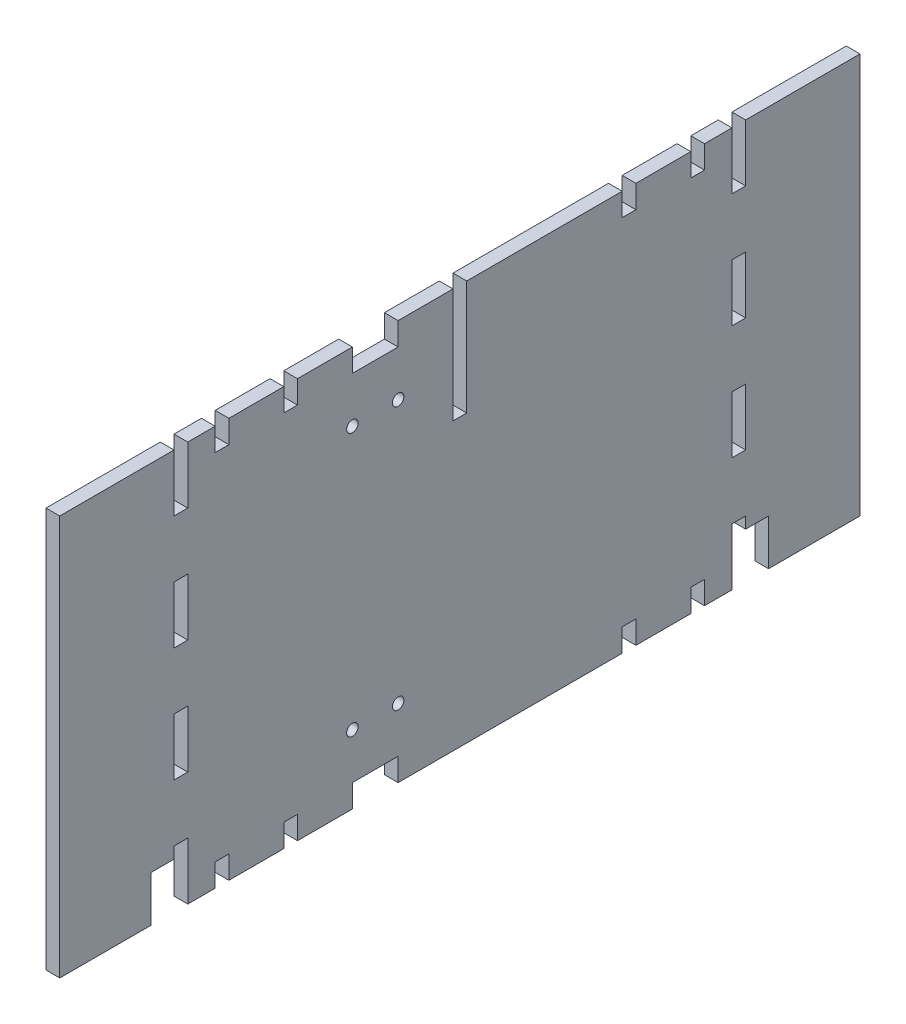
SolidWorks part; units mm, degrees
ref_plane "Front" through (0, 0, 0) normal (0, 0, 1) x (1, 0, 0)
ref_plane "Top" through (0, 0, 0) normal (0, 1, 0) x (1, 0, 0)
ref_plane "Right" through (0, 0, 0) normal (1, 0, 0) x (0, 0, -1)
sketch "Sketch1" plane through (0, 0, 0) normal (1, 0, 0) x (0, 0, -1)
  line L1 (0, 0) -> (-350, 0)
  line L2 (0, 0) -> (0, 175)
  line L3 (0, 175) -> (-350, 175)
  line L4 (-350, 0) -> (-350, 175)
  dimension "D1" = 350
  dimension "D2" = 175
extrude "Boss-Extrude1" add sketch "Sketch1" along normal blind 6
ref_plane "Plane1" through (0, 0, 175) normal (0, 0, 1) x (1, 0, 0)
sketch "Sketch3" plane through (6, 0, 0) normal (1, 0, 0) x (0, 0, -1)
  line L0 (-350, 175) -> (-350, 0) construction
  line L1 (-300, 175) -> (-294, 175)
  line L2 (-300, 175) -> (-300, 150)
  line L3 (-300, 150) -> (-294, 150)
  line L4 (-294, 175) -> (-294, 150)
  line L5 (0, 175) -> (-350, 175) construction
  dimension "D1" = 6
  dimension "D2" = 25
  dimension "D3" = 50
extrude "Cut-Extrude1" cut sketch "Sketch3" against normal through all
pattern_linear "LPattern1" count 4 spacing 50 along (0, -1, 0) of "Cut-Extrude1"
sketch "Sketch4" plane through (6, 0, 0) normal (1, 0, 0) x (0, 0, -1)
  line L0 (0, 175) -> (-294, 175) construction
  line L1 (-282, 175) -> (-276, 175)
  line L2 (-282, 175) -> (-282, 165)
  line L3 (-282, 165) -> (-276, 165)
  line L4 (-276, 175) -> (-276, 165)
  line L5 (-294, 150) -> (-294, 175) construction
  dimension "D1" = 6
  dimension "D2" = 12
  dimension "D3" = 10
extrude "Cut-Extrude2" cut sketch "Sketch4" against normal through all
pattern_linear "LPattern2" count 2 spacing 165 along (0, -1, 0) of "Cut-Extrude2"
sketch "Sketch5" plane through (6, 0, 0) normal (1, 0, 0) x (0, 0, -1)
  line L0 (0, 175) -> (-276, 175) construction
  line L1 (-252, 175) -> (-246, 175)
  line L2 (-252, 175) -> (-252, 165)
  line L3 (-252, 165) -> (-246, 165)
  line L4 (-246, 175) -> (-246, 165)
  line L5 (-276, 165) -> (-276, 175) construction
  line L6 (-282, 165) -> (-276, 165) construction
  dimension "D1" = 24
  dimension "D2" = 6
extrude "Cut-Extrude3" cut sketch "Sketch5" against normal through all
pattern_linear "LPattern3" count 2 spacing 165 along (0, -1, 0) of "Cut-Extrude3"
sketch "Sketch6" plane through (6, 0, 0) normal (1, 0, 0) x (0, 0, -1)
  line L0 (0, 175) -> (-246, 175) construction
  line L1 (-178, 175) -> (-172, 175)
  line L2 (-178, 175) -> (-178, 125)
  line L3 (-178, 125) -> (-172, 125)
  line L4 (-172, 175) -> (-172, 125)
  line L5 (-175, 3.3) -> (-175, -3.3) construction
  point P6 (-175, 175)
  dimension "D1" = 6
  dimension "D2" = 50
extrude "Cut-Extrude4" cut sketch "Sketch6" against normal blind 10
sketch "Sketch7" plane through (6, 0, 0) normal (1, 0, 0) x (0, 0, -1)
  line L0 (-178, 175) -> (-246, 175) construction
  line L1 (-222, 175) -> (-202, 175)
  line L2 (-222, 175) -> (-222, 165)
  line L3 (-222, 165) -> (-202, 165)
  line L4 (-202, 175) -> (-202, 165)
  point P6 (-212, 175)
  point P7 (-212, 175)
  dimension "D1" = 10
  dimension "D2" = 20
extrude "Cut-Extrude5" cut sketch "Sketch7" against normal blind 10
pattern_linear "LPattern4" count 2 spacing 165 along (0, -1, 0) of "Cut-Extrude5"
sketch "Sketch8" plane through (6, 0, 0) normal (1, 0, 0) x (0, 0, -1)
  line L0 (-222, 145) -> (-202, 145) construction
  line L1 (-222, 30) -> (-202, 30) construction
  line L2 (-212, 165) -> (-212, 10) construction
  line L3 (-222, 165) -> (-202, 165) construction
  line L4 (-202, 10) -> (-222, 10) construction
  circle A0 centre (-222, 145) radius 2.5
  circle A1 centre (-202, 145) radius 2.5
  circle A2 centre (-222, 30) radius 2.5
  circle A3 centre (-202, 30) radius 2.5
  point P8 (-212, 145)
  point P15 (-212, 30)
  dimension "D3" = 5
  dimension "D1" = 20
  dimension "D2" = 20
  dimension "D4" = 20
extrude "Cut-Extrude6" cut sketch "Sketch8" against normal blind 10
sketch "Sketch9" plane through (6, 0, 0) normal (1, 0, 0) x (0, 0, -1)
  line L1 (-300, 20) -> (-310, 20)
  line L2 (-300, 20) -> (-300, 0)
  line L3 (-300, 0) -> (-310, 0)
  line L4 (-310, 20) -> (-310, 0)
  line L5 (-350, 0) -> (-300, 0) construction
  line L6 (-300, 25) -> (-300, 0) construction
  dimension "D1" = 10
  dimension "D2" = 20
extrude "Cut-Extrude7" cut sketch "Sketch9" against normal blind 10
mirror "Mirror1" about plane through (0, 0, 175) normal (0, 0, 1) of "LPattern3", "LPattern2", "LPattern1", "Cut-Extrude7", "Cut-Extrude1", "Cut-Extrude2", "Cut-Extrude3"
equation "\"`10\"=11.8105"
